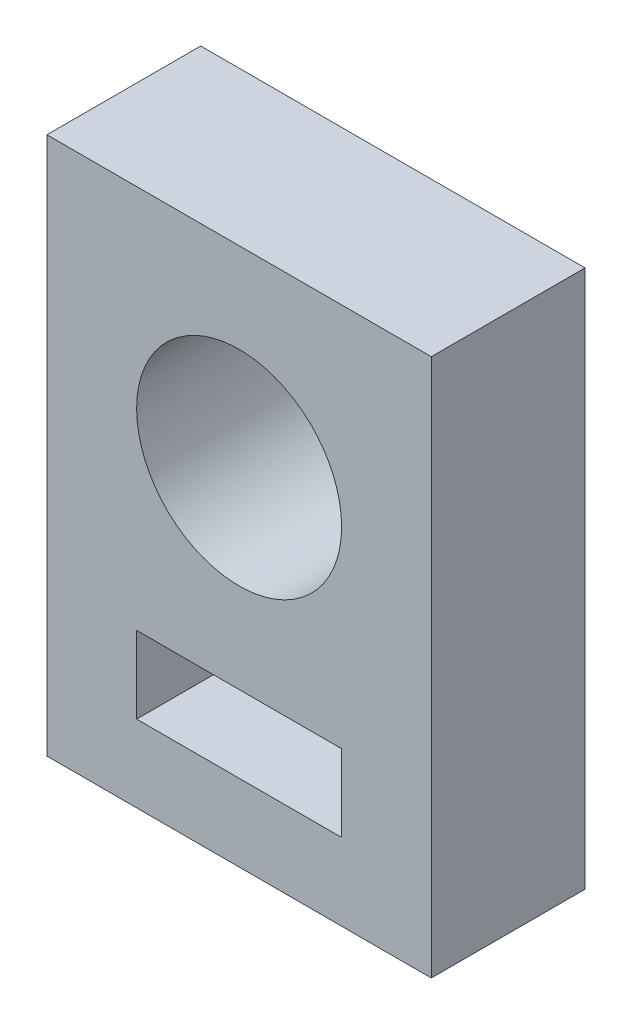
SolidWorks part; units mm, degrees
ref_plane "Front Plane" through (0, 0, 0) normal (0, 0, 1) x (1, 0, 0)
ref_plane "Top Plane" through (0, 0, 0) normal (0, 1, 0) x (1, 0, 0)
ref_plane "Right Plane" through (0, 0, 0) normal (1, 0, 0) x (0, 0, -1)
sketch "Sketch1" plane through (0, 0, 0) normal (0, 0, 1) x (1, 0, 0)
  line L5 (0, -1) -> (0, -4.5) construction
  line L7 (-7.5, -10.5) -> (7.5, -10.5)
  line L32 (-7.5, -10.5) -> (-7.5, 10.5)
  line L54 (-7.5, 10.5) -> (7.5, 10.5)
  line L59 (7.5, -10.5) -> (7.5, 10.5)
  line L60 (-7.5, -10.5) -> (7.5, 10.5) construction
  line L67 (-7.5, 10.5) -> (7.5, -10.5) construction
  line L76 (-4, -7.5) -> (4, -7.5)
  line L77 (-4, -7.5) -> (-4, -4.5)
  line L78 (-4, -4.5) -> (4, -4.5)
  line L79 (4, -7.5) -> (4, -4.5)
  line L80 (-4, -7.5) -> (4, -4.5) construction
  line L81 (-4, -4.5) -> (4, -7.5) construction
  circle A1 centre (0, 3) radius 4
  point P0 (0, 0)
  point P8 (0, -6)
  dimension "D1" = 21
  dimension "D3" = 8
  dimension "D2" = 15
  dimension "D4" = 7.5
  dimension "D5" = 7.5
  dimension "D6" = 8
  dimension "D7" = 3
  dimension "D8" = 3.5
  dimension "D9" = 3
  dimension "D10" = 3.5
extrude "Boss-Extrude1" add sketch "Sketch1" along normal blind 6
